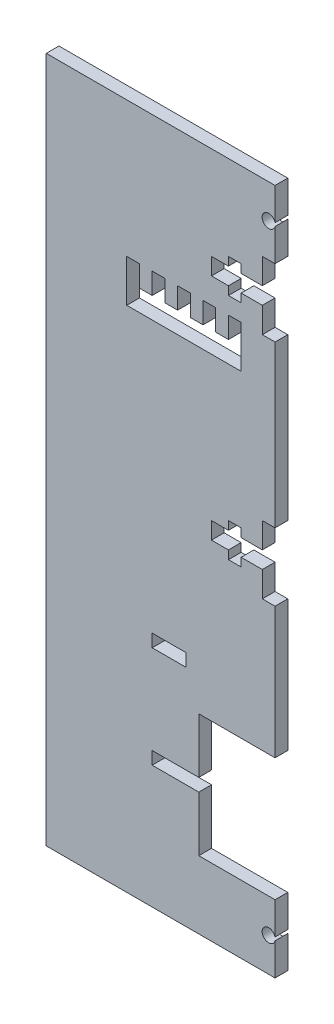
SolidWorks part; units mm, degrees
ref_plane "前视" through (0, 0, 0) normal (0, 0, 1) x (1, 0, 0)
ref_plane "上视" through (0, 0, 0) normal (0, 1, 0) x (1, 0, 0)
ref_plane "右视" through (0, 0, 0) normal (1, 0, 0) x (0, 0, -1)
sketch "草图1" plane through (0, 0, 0) normal (0, 0, 1) x (1, 0, 0)
  line L0 (0, 146) -> (0, 140)
  line L1 (0, 0) -> (-51, 0)
  line L2 (-51, 0) -> (-51, 162)
  line L3 (-51, 162) -> (0, 162)
  line L4 (0, 162) -> (3, 162)
  line L5 (3, 162) -> (3, 154.3905)
  line L6 (3, 146) -> (0, 146)
  line L7 (0, 0) -> (3, 0)
  line L8 (3, 0) -> (3, 7.6095)
  line L9 (3, 16) -> (0, 16)
  line L10 (0, 130) -> (3, 130)
  line L11 (3, 130) -> (3, 92)
  line L12 (3, 92) -> (0, 92)
  line L13 (0, 16) -> (-15, 16)
  line L14 (-15, 16) -> (-15, 29)
  line L15 (-15, 45) -> (0, 45)
  line L16 (15.9655, 138) -> (-24.4172, 138) construction
  line L17 (26.8934, 84) -> (-22.3685, 84) construction
  line L18 (-12, 136) -> (-12, 140)
  line L19 (-12, 140) -> (-8, 140)
  line L20 (-8, 140) -> (-8, 142)
  line L21 (-8, 142) -> (-5, 142)
  line L22 (-5, 142) -> (-5, 140)
  line L23 (-5, 140) -> (0, 140)
  line L24 (-8, 86) -> (-12, 86)
  line L25 (-12, 86) -> (-12, 82)
  line L26 (-8, 86) -> (-8, 88)
  line L27 (-8, 88) -> (-5, 88)
  line L28 (-5, 88) -> (-5, 86)
  line L29 (-5, 86) -> (0, 86)
  line L30 (-5, 136) -> (0, 136)
  line L31 (-5, 134) -> (-5, 136)
  line L32 (-8, 134) -> (-5, 134)
  line L33 (-8, 136) -> (-8, 134)
  line L34 (-12, 136) -> (-8, 136)
  line L35 (-5, 82) -> (0, 82)
  line L36 (-5, 80) -> (-5, 82)
  line L37 (-8, 80) -> (-5, 80)
  line L38 (-8, 82) -> (-8, 80)
  line L39 (-8, 82) -> (-12, 82)
  line L40 (3, 153.6095) -> (3, 146)
  line L41 (0, 136) -> (0, 130)
  line L42 (0, 92) -> (0, 86)
  line L43 (0, 82) -> (0, 76)
  line L44 (3, 8.3905) -> (3, 16)
  line L45 (-8, 125) -> (-8, 130)
  line L46 (-18, 32) -> (-15, 32)
  line L47 (-26, 56) -> (-18, 56)
  line L48 (-26, 56) -> (-26, 53)
  line L49 (-26, 53) -> (-18, 53)
  line L50 (-8, 130) -> (-5, 130)
  line L51 (-5, 130) -> (-5, 120)
  line L52 (-18, 56) -> (-18, 53)
  line L53 (-26, 32) -> (-18, 32)
  line L54 (-26, 32) -> (-26, 29)
  line L55 (-26, 29) -> (-18, 29)
  line L56 (0, 45) -> (3, 45)
  line L57 (-18, 29) -> (-15, 29)
  line L58 (-15, 32) -> (-15, 45)
  line L59 (3, 45) -> (3, 76)
  line L60 (3, 76) -> (0, 76)
  line L67 (-32, 120) -> (-32, 130)
  line L68 (-32, 120) -> (-5, 120)
  line L69 (-29, 130) -> (-32, 130)
  line L70 (-29, 125) -> (-29, 130)
  line L71 (-26, 125) -> (-29, 125)
  line L72 (-26, 130) -> (-26, 125)
  line L73 (-23, 130) -> (-26, 130)
  line L74 (-23, 125) -> (-23, 130)
  line L75 (-20, 125) -> (-23, 125)
  line L76 (-20, 130) -> (-20, 125)
  line L77 (-17, 130) -> (-20, 130)
  line L78 (-17, 125) -> (-17, 130)
  line L79 (-14, 125) -> (-17, 125)
  line L80 (-14, 130) -> (-14, 125)
  line L81 (-11, 130) -> (-14, 130)
  line L82 (-11, 125) -> (-11, 130)
  line L83 (-8, 125) -> (-11, 125)
  arc A0 (3, 154.3905) -> (3, 153.6095) centre (1.5, 154) ccw
  arc A1 (3, 8.3905) -> (3, 7.6095) centre (1.5, 8) ccw
  point P41 (-12, 138)
  point P47 (-12, 84)
  dimension "D11" = 2
  dimension "D12" = 2
  dimension "D13" = 2
  dimension "D25" = 1.55
  dimension "D26" = 1.55
  dimension "D46" = 8
  dimension "D48" = 1.5
  dimension "D2" = 16
  dimension "D3" = 3
  dimension "D4" = 16
  dimension "D5" = 16
  dimension "D6" = 3
  dimension "D7" = 3
  dimension "D8" = 38
  dimension "D9" = 29
  dimension "D10" = 15
  dimension "D14" = 3
  dimension "D15" = 5
  dimension "D16" = 12
  dimension "D17" = 8
  dimension "D18" = 2
  dimension "D19" = 2
  dimension "D20" = 2
  dimension "D21" = 3
  dimension "D22" = 5
  dimension "D23" = 12
  dimension "D24" = 8
  dimension "D27" = 51
  dimension "D28" = 10
  dimension "D29" = 5
  dimension "D30" = 5
  dimension "D31" = 5
  dimension "D32" = 5
  dimension "D33" = 3
  dimension "D34" = 3
  dimension "D35" = 3
  dimension "D36" = 3
  dimension "D37" = 3
  dimension "D38" = 3
  dimension "D39" = 3
  dimension "D40" = 3
  dimension "D41" = 3
  dimension "D42" = 5
  dimension "D43" = 5
  dimension "D44" = 162
  dimension "D45" = 1.5
  dimension "D47" = 8
  dimension "D49" = 29
  dimension "D50" = 53
  dimension "D51" = 3
  dimension "D52" = 3
  dimension "D53" = 8
  dimension "D54" = 8
  dimension "D55" = 18
  dimension "D56" = 3
  dimension "D57" = 51
  dimension "D58" = 3
  dimension "D59" = 8
extrude "凸台-拉伸1" add sketch "草图1" along normal blind 3
